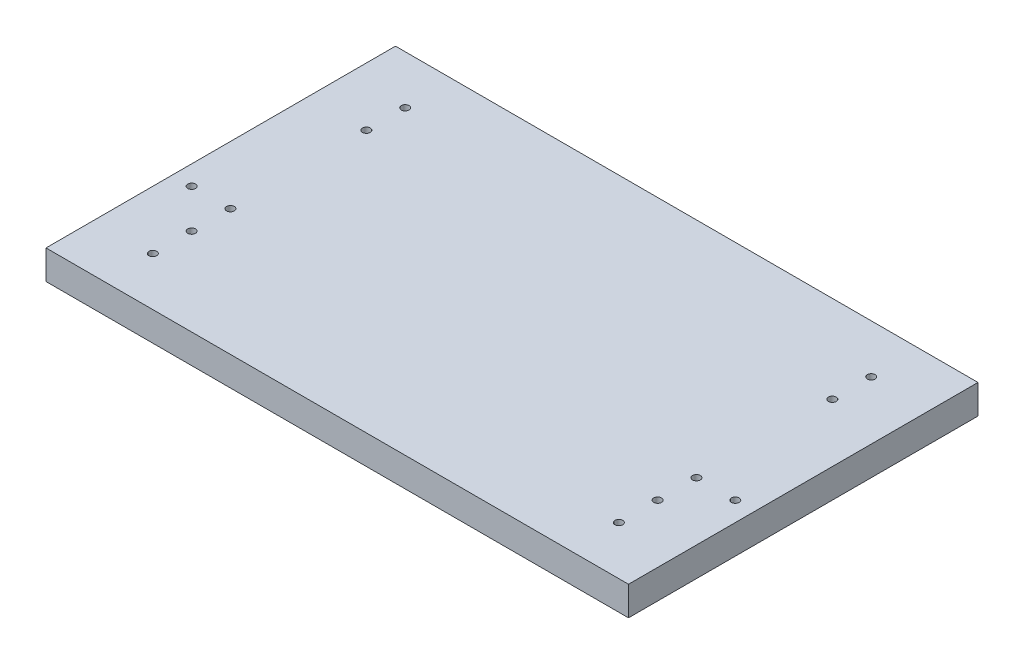
SolidWorks part; units mm, degrees
ref_plane "Alzado" through (0, 0, 0) normal (0, 0, 1) x (1, 0, 0)
ref_plane "Planta" through (0, 0, 0) normal (0, 1, 0) x (1, 0, 0)
ref_plane "Vista lateral" through (0, 0, 0) normal (1, 0, 0) x (0, 0, -1)
sketch "Croquis1" plane through (0, 0, 0) normal (0, 1, 0) x (1, 0, 0)
  line L1 (-150, -90) -> (150, -90)
  line L2 (-150, -90) -> (-150, 90)
  line L3 (-150, 90) -> (150, 90)
  line L4 (150, -90) -> (150, 90)
  line L5 (-150, -90) -> (150, 90) construction
  line L6 (-150, 90) -> (150, -90) construction
  point P0 (0, 0)
  dimension "D1" = 300
  dimension "D2" = 180
extrude "Saliente-Extruir1" add sketch "Croquis1" along normal blind 15
sketch "Croquis2" plane through (0, 15, 0) normal (0, 1, 0) x (1, 0, 0)
  line L0 (150, 90) -> (-150, 90) construction
  line L1 (-150, -90) -> (150, -90) construction
  line L2 (-150, 90) -> (-150, -90) construction
  line L3 (150, -90) -> (150, 90) construction
  circle A0 centre (-120, -65) radius 2
  circle A1 centre (-120, -45) radius 2
  circle A2 centre (120, -65) radius 2
  circle A3 centre (120, -45) radius 2
  circle A4 centre (-140, -25) radius 2
  circle A5 centre (-120, -25) radius 2
  circle A6 centre (120, -25) radius 2
  circle A7 centre (140, -25) radius 2
  circle A8 centre (-120, 65) radius 2
  circle A9 centre (-120, 45) radius 2
  circle A10 centre (120, 45) radius 2
  circle A11 centre (120, 65) radius 2
  dimension "D1" = 25
  dimension "D2" = 0
  dimension "D3" = 25
  dimension "D4" = 0
  dimension "D7" = 10
  dimension "D8" = 20
  dimension "D9" = 30
  dimension "D10" = 10
  dimension "D15" = 25
  dimension "D19" = 45
  dimension "D5" = 30
  dimension "D6" = 30
  dimension "D11" = 65
  dimension "D12" = 0
  dimension "D13" = 65
  dimension "D14" = 0
  dimension "D16" = 20
  dimension "D17" = 25
  dimension "D18" = 20
  dimension "D20" = 45
extrude "Cortar-Extruir1" cut sketch "Croquis2" against normal blind 10
